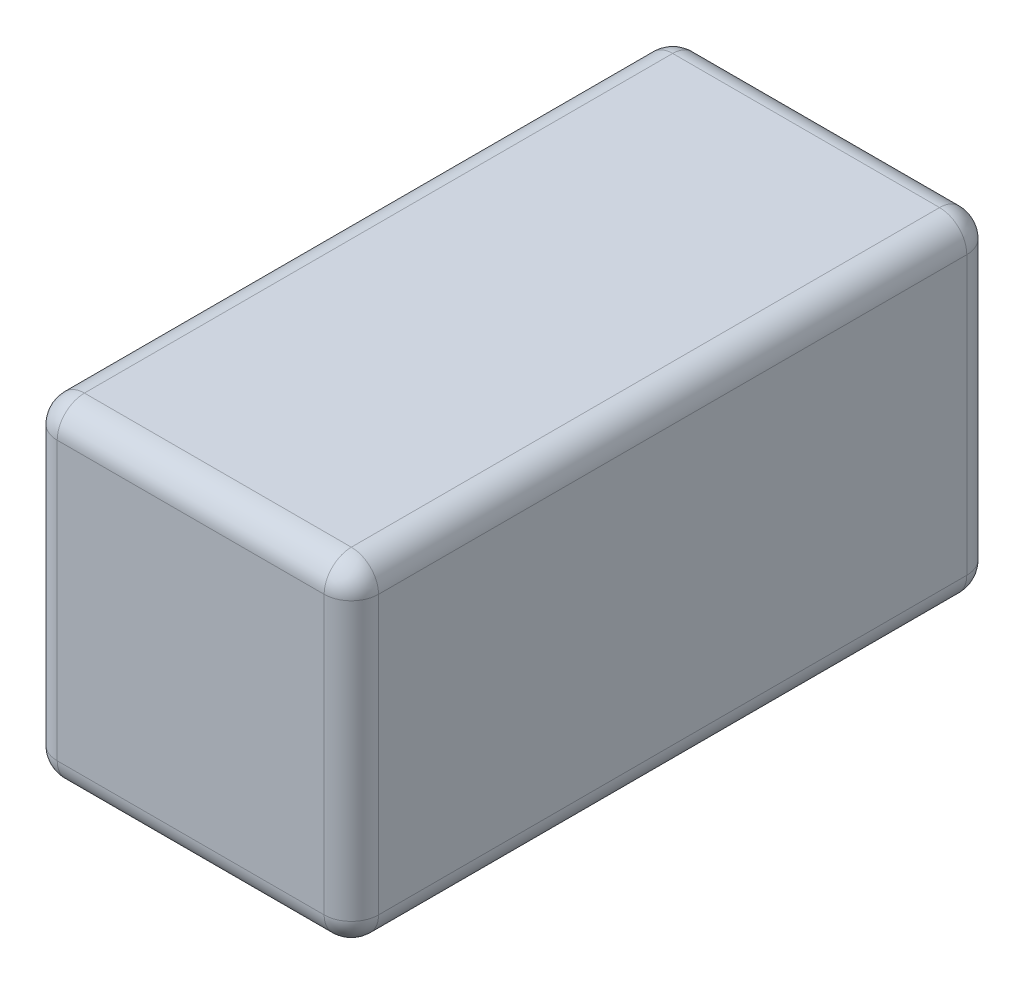
SolidWorks part; units mm, degrees
ref_plane "Front Plane" through (0, 0, 0) normal (0, 0, 1) x (1, 0, 0)
ref_plane "Top Plane" through (0, 0, 0) normal (0, 1, 0) x (1, 0, 0)
ref_plane "Right Plane" through (0, 0, 0) normal (1, 0, 0) x (0, 0, -1)
sketch "Sketch1" plane through (0, 0, 0) normal (0, 0, 1) x (1, 0, 0)
  line L1 (15, -15.5) -> (-15, -15.5)
  line L2 (15, -15.5) -> (15, 15.5)
  line L3 (15, 15.5) -> (-15, 15.5)
  line L4 (-15, -15.5) -> (-15, 15.5)
  line L5 (15, -15.5) -> (-15, 15.5) construction
  line L6 (15, 15.5) -> (-15, -15.5) construction
  point P0 (0, 0)
  dimension "D1" = 30
  dimension "D2" = 31
extrude "Boss-Extrude1" add sketch "Sketch1" along normal blind 60
fillet "Fillet1" radius 2.54 12 edges at (-15, 0, 0) (-15, 0, 60) (-15, -15.5, 30) (0, -15.5, 60) (0, -15.5, 0) (15, -15.5, 30) (15, 0, 60) (15, 0, 0) (15, 15.5, 30) (0, 15.5, 60) (-15, 15.5, 30) (0, 15.5, 0)
